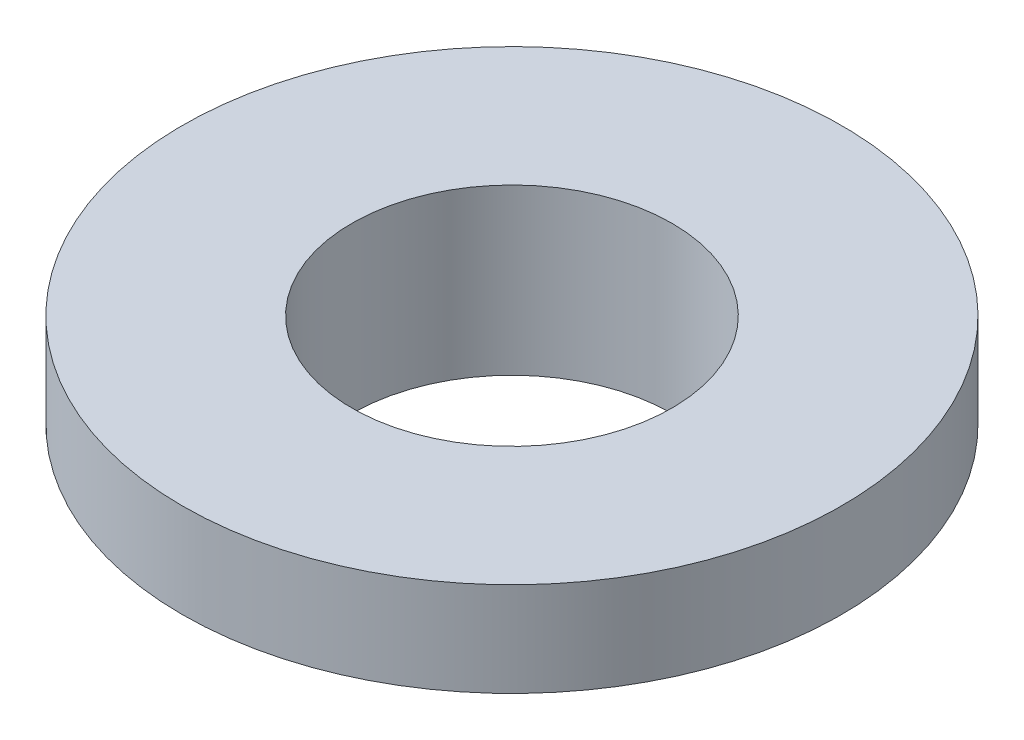
SolidWorks part; units mm, degrees
ref_plane "Front Plane" through (0, 0, 0) normal (0, 0, 1) x (1, 0, 0)
ref_plane "Top Plane" through (0, 0, 0) normal (0, 1, 0) x (1, 0, 0)
ref_plane "Right Plane" through (0, 0, 0) normal (1, 0, 0) x (0, 0, -1)
sketch "Sketch1" plane through (0, 0, 0) normal (0, 1, 0) x (1, 0, 0)
  circle A0 centre (0, 0) radius 4.318
  circle A1 centre (0, 0) radius 5.715
  dimension "D1" = 8.636
  dimension "D2" = 11.43
extrude "Boss-Extrude1" add sketch "Sketch1" along normal blind 1.905
sketch "Sketch2" plane through (0, 1.905, 0) normal (0, 1, 0) x (1, 0, 0)
  circle A0 centre (0, 0) radius 4.318
  circle A1 centre (0, 0) radius 8.89
  dimension "D1" = 17.78
extrude "Boss-Extrude2" add sketch "Sketch2" along normal blind 2.54
